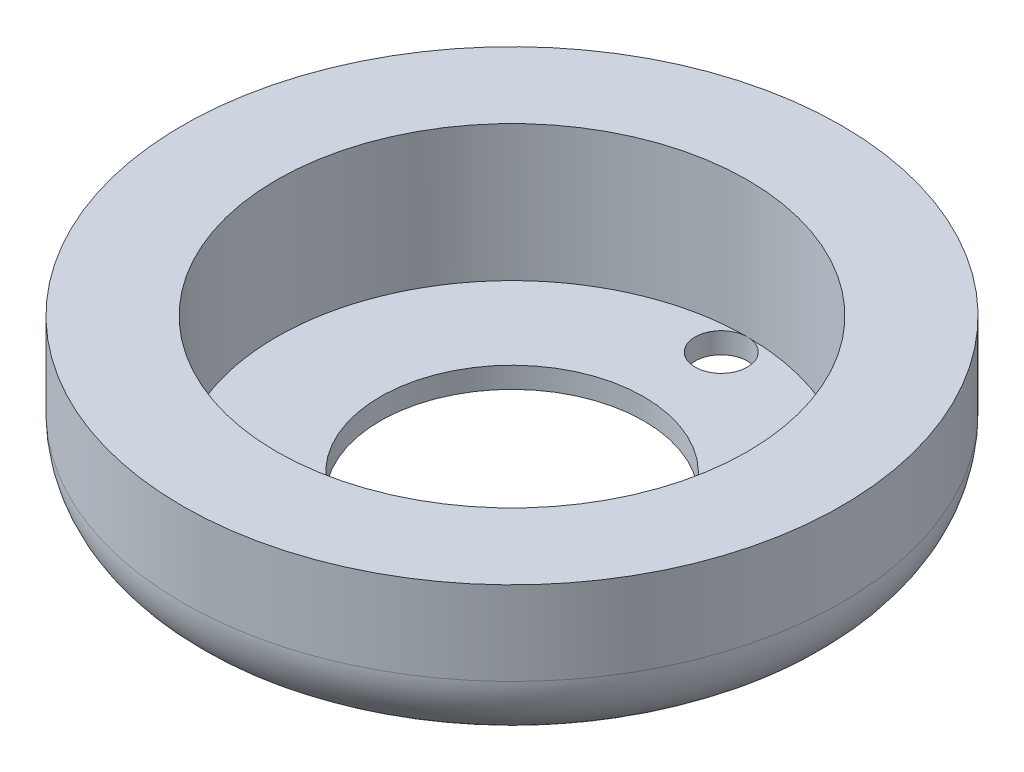
SolidWorks part; units mm, degrees
ref_plane "Front Plane" through (0, 0, 0) normal (0, 0, 1) x (1, 0, 0)
ref_plane "Top Plane" through (0, 0, 0) normal (0, 1, 0) x (1, 0, 0)
ref_plane "Right Plane" through (0, 0, 0) normal (1, 0, 0) x (0, 0, -1)
sketch "Sketch1" plane through (0, 0, 0) normal (0, 1, 0) x (1, 0, 0)
  circle A0 centre (0, 0) radius 31.5
  dimension "D1" = 63
extrude "Boss-Extrude1" add sketch "Sketch1" along normal blind 15
sketch "Sketch2" plane through (0, 15, 0) normal (0, 1, 0) x (1, 0, 0)
  circle A0 centre (0, 0) radius 22.5
  circle A1 centre (0, 0) radius 31.5 construction
  dimension "D1" = 9
extrude "Cut-Extrude1" cut sketch "Sketch2" against normal blind 13
sketch "Sketch3" plane through (0, 0, 0) normal (0, -1, 0) x (1, 0, 0)
  line L0 (0, 0) -> (0, -20)
  line L1 (0, 0) -> (0, 20)
  circle A0 centre (0, 0) radius 12.6
  circle A1 centre (0, 20) radius 2.5
  circle A2 centre (0, -20) radius 2.5
  dimension "D1" = 25.2
  dimension "D4" = 5
  dimension "D5" = 5
  dimension "D2" = 20
  dimension "D3" = 20
extrude "Cut-Extrude2" cut sketch "Sketch3" against normal blind 13 contours A2 | A0 | A1
fillet "Fillet1" radius 7 1 edges at (0, 0, 31.5)
